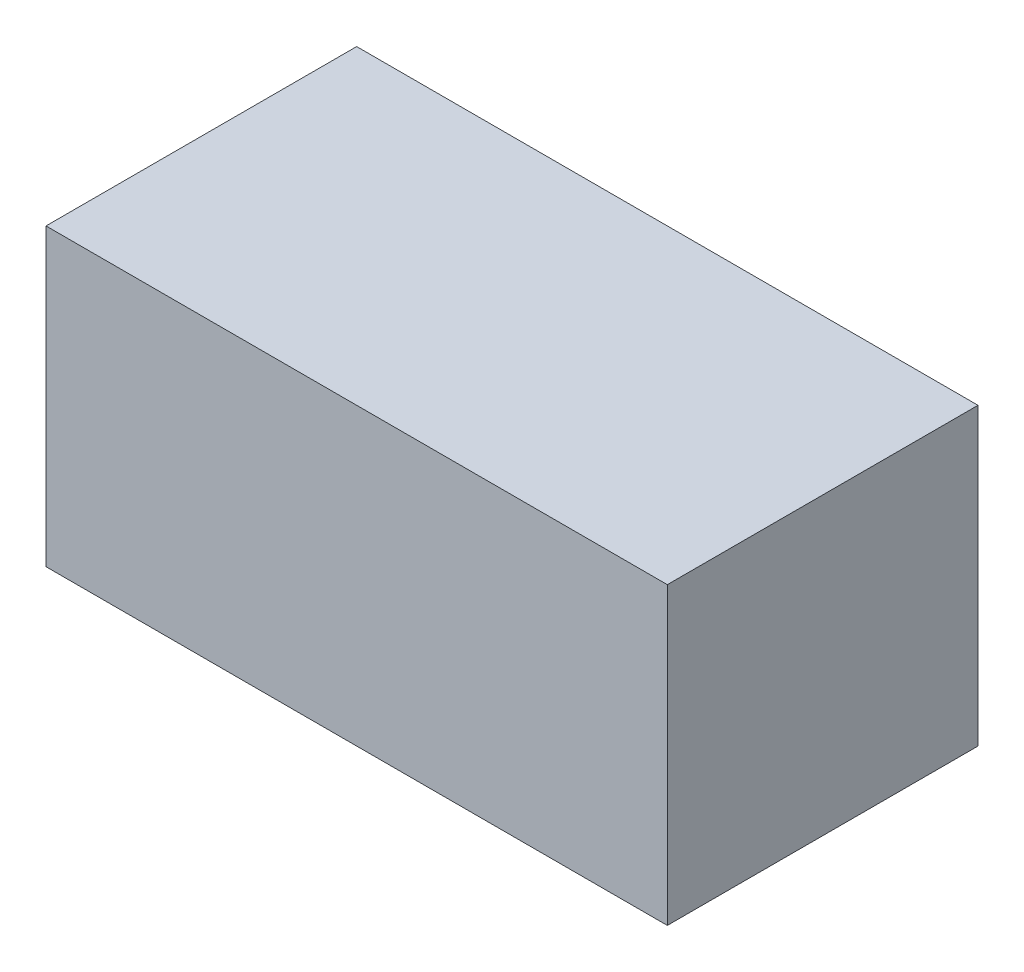
SolidWorks part; units mm, degrees
ref_plane "Front Plane" through (0, 0, 0) normal (0, 0, 1) x (1, 0, 0)
ref_plane "Top Plane" through (0, 0, 0) normal (0, 1, 0) x (1, 0, 0)
ref_plane "Right Plane" through (0, 0, 0) normal (1, 0, 0) x (0, 0, -1)
sketch "Sketch1" plane through (0, 0, 0) normal (0, 1, 0) x (1, 0, 0)
  line L1 (0, 0) -> (40, 0)
  line L2 (0, 0) -> (0, 20)
  line L3 (0, 20) -> (40, 20)
  line L4 (40, 0) -> (40, 20)
extrude "Boss-Extrude1" add sketch "Sketch1" along normal blind 19
